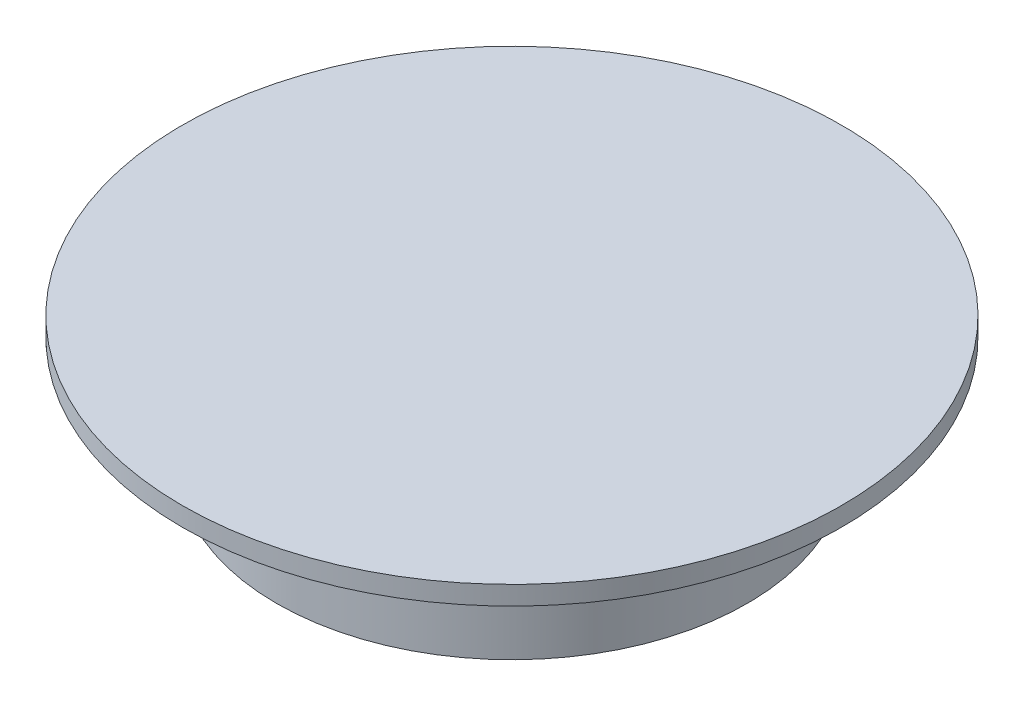
SolidWorks part; units mm, degrees
ref_plane "Front Plane" through (0, 0, 0) normal (0, 0, 1) x (1, 0, 0)
ref_plane "Top Plane" through (0, 0, 0) normal (0, 1, 0) x (1, 0, 0)
ref_plane "Right Plane" through (0, 0, 0) normal (1, 0, 0) x (0, 0, -1)
sketch "Sketch1" plane through (0, 0, 0) normal (1, 0, 0) x (0, 0, -1)
  line L0 (0, 5.9024) -> (0, -18.2784) construction
  line L1 (-35, 7) -> (-35, 5)
  line L2 (-35, 5) -> (-25, 5)
  line L3 (-25, 5) -> (-25, -7)
  line L4 (-25, -7) -> (0, -7)
  line L5 (-35, 7) -> (0, 7)
  line L6 (0, 7) -> (0, -7)
  point P8 (0, -18.2784)
  point P10 (0, 3.9331)
  point P11 (0, 0)
  dimension "D1" = 2
  dimension "D2" = 70
  dimension "D3" = 50
  dimension "D4" = 12
revolve "Revolve1" add sketch "Sketch1" angle 360 about L0
